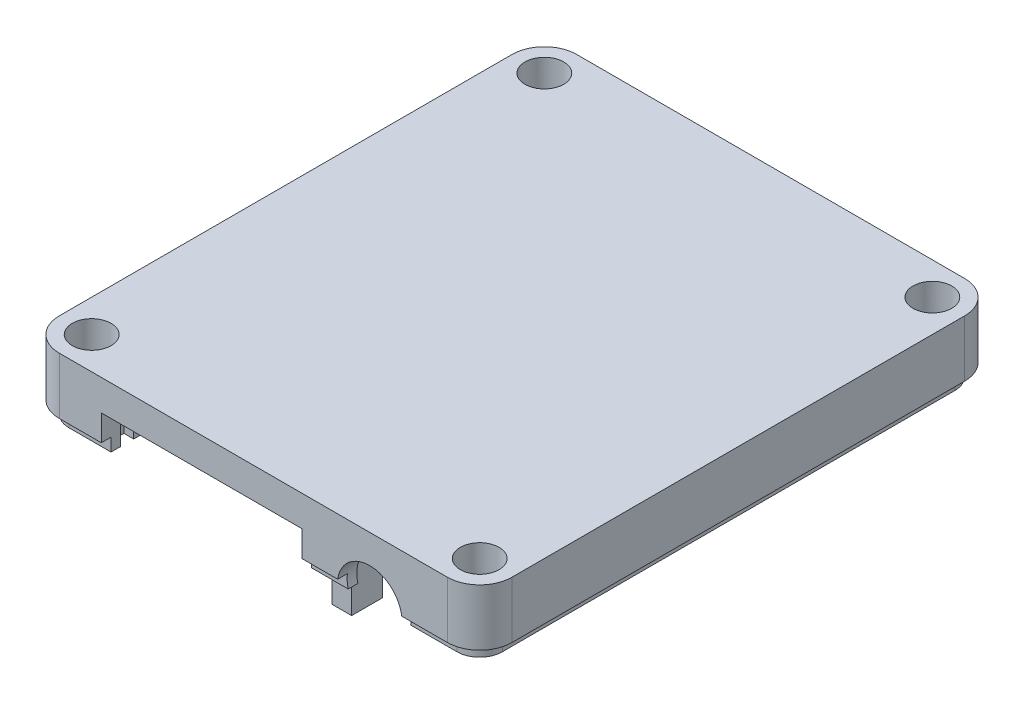
SolidWorks part; units mm, degrees
ref_plane "Front Plane" through (0, 0, 0) normal (0, 0, 1) x (1, 0, 0)
ref_plane "Top Plane" through (0, 0, 0) normal (0, 1, 0) x (1, 0, 0)
ref_plane "Right Plane" through (0, 0, 0) normal (1, 0, 0) x (0, 0, -1)
sketch "Sketch1" plane through (0, 0, 0) normal (0, 1, 0) x (1, 0, 0)
  line L1 (35, -40) -> (-35, -40)
  line L2 (35, -40) -> (35, 40)
  line L3 (35, 40) -> (-35, 40)
  line L4 (-35, -40) -> (-35, 40)
  line L5 (35, -40) -> (-35, 40) construction
  line L6 (35, 40) -> (-35, -40) construction
  point P0 (0, 0)
  dimension "D1" = 70
  dimension "D2" = 80
extrude "Boss-Extrude1" add sketch "Sketch1" along normal blind 21.5
fillet "Fillet1" radius 5 4 edges at (-35, 10.75, -40) (35, 10.75, 40) (-35, 10.75, 40) (35, 10.75, -40)
shell "Shell1" thickness 3
sketch "Sketch3" plane through (0, 21.5, 0) normal (0, 1, 0) x (1, 0, 0)
  circle A0 centre (-30, 35) radius 5
  circle A1 centre (30, 35) radius 5
  circle A2 centre (30, -35) radius 5
  circle A3 centre (-30, -35) radius 5
  arc A4 (-30, 40) -> (-35, 35) centre (-30, 35) ccw construction
  arc A5 (35, 35) -> (30, 40) centre (30, 35) ccw construction
  arc A6 (30, -40) -> (35, -35) centre (30, -35) ccw construction
  arc A7 (-35, -35) -> (-30, -40) centre (-30, -35) ccw construction
extrude "Boss-Extrude2" add sketch "Sketch3" against normal through all
sketch "Sketch2" plane through (0, 0, 0) normal (1, 0, 0) x (0, 0, -1)
  line L0 (-40, 10.75) -> (51.5624, 10.75)
  line L1 (-40, 0) -> (-40, 21.5) construction
split "Split2" trim tools "Sketch2" bodies to split 104 resulting bodies 105 106
sketch "Sketch4" plane through (0, 21.5, 0) normal (0, 1, 0) x (1, 0, 0)
  circle A0 centre (-30, 35) radius 1
  circle A1 centre (30, 35) radius 1
  circle A2 centre (30, -35) radius 1
  circle A3 centre (-30, -35) radius 1
  dimension "D1" = 2
extrude "Cut-Extrude1" cut sketch "Sketch4" against normal through all
sketch "Sketch6" plane through (0, 10.75, 0) normal (0, -1, 0) x (1, 0, 0)
  line L8 (-30, -38.5) -> (30, -38.5)
  line L9 (33.5, -35) -> (33.5, 35)
  line L10 (30, 38.5) -> (-30, 38.5)
  line L11 (-33.5, 35) -> (-33.5, -35)
  line L12 (-30, -38.5) -> (30, -38.5)
  line L13 (33.5, -35) -> (33.5, 35)
  line L14 (30, 38.5) -> (-30, 38.5)
  line L15 (-33.5, 35) -> (-33.5, -35)
  arc A8 (-33.5, -35) -> (-30, -38.5) centre (-30, -35) ccw
  arc A9 (30, -38.5) -> (33.5, -35) centre (30, -35) ccw
  arc A10 (33.5, 35) -> (30, 38.5) centre (30, 35) ccw
  arc A11 (-30, 38.5) -> (-33.5, 35) centre (-30, 35) ccw
  arc A12 (-33.5, -35) -> (-30, -38.5) centre (-30, -35) ccw
  arc A13 (30, -38.5) -> (33.5, -35) centre (30, -35) ccw
  arc A14 (33.5, 35) -> (30, 38.5) centre (30, 35) ccw
  arc A15 (-30, 38.5) -> (-33.5, 35) centre (-30, 35) ccw
  dimension "D1" = 1.5
extrude "Cut-Extrude3" cut sketch "Sketch6" against normal blind 2 flip side to cut
sketch "Sketch7" plane through (0, 10.75, 0) normal (0, 1, 0) x (1, 0, 0)
  line L0 (-30, 40) -> (30, 40) construction
  line L1 (35, 35) -> (35, -35) construction
  line L2 (30, -40) -> (-30, -40) construction
  line L3 (-35, -35) -> (-35, 35) construction
  line L4 (-30, 40) -> (30, 40)
  line L5 (35, 35) -> (35, -35)
  line L6 (30, -40) -> (-30, -40)
  line L7 (-35, -35) -> (-35, 35)
  line L16 (30, 38.7) -> (-30, 38.7)
  line L17 (33.7, -35) -> (33.7, 35)
  line L18 (-30, -38.7) -> (30, -38.7)
  line L19 (-33.7, 35) -> (-33.7, -35)
  line L20 (30, 38.7) -> (-30, 38.7)
  line L21 (33.7, -35) -> (33.7, 35)
  line L22 (-30, -38.7) -> (30, -38.7)
  line L23 (-33.7, 35) -> (-33.7, -35)
  arc A0 (-30, 40) -> (-35, 35) centre (-30, 35) ccw construction
  arc A1 (35, 35) -> (30, 40) centre (30, 35) ccw construction
  arc A2 (30, -40) -> (35, -35) centre (30, -35) ccw construction
  arc A3 (-35, -35) -> (-30, -40) centre (-30, -35) ccw construction
  arc A4 (-30, 40) -> (-35, 35) centre (-30, 35) ccw
  arc A5 (35, 35) -> (30, 40) centre (30, 35) ccw
  arc A6 (30, -40) -> (35, -35) centre (30, -35) ccw
  arc A7 (-35, -35) -> (-30, -40) centre (-30, -35) ccw
  arc A16 (-30, 38.7) -> (-33.7, 35) centre (-30, 35) ccw
  arc A17 (33.7, 35) -> (30, 38.7) centre (30, 35) ccw
  arc A18 (30, -38.7) -> (33.7, -35) centre (30, -35) ccw
  arc A19 (-33.7, -35) -> (-30, -38.7) centre (-30, -35) ccw
  arc A20 (-30, 38.7) -> (-33.7, 35) centre (-30, 35) ccw
  arc A21 (33.7, 35) -> (30, 38.7) centre (30, 35) ccw
  arc A22 (30, -38.7) -> (33.7, -35) centre (30, -35) ccw
  arc A23 (-33.7, -35) -> (-30, -38.7) centre (-30, -35) ccw
  dimension "D1" = 0.2
extrude "Boss-Extrude3" add sketch "Sketch7" along normal offset from surface (1.8 mm away) 0.2 up to face at (0, 12.75, 0)
sketch "Sketch8" plane through (-35, 0, 0) normal (-1, 0, 0) x (0, 0, 1)
  line L1 (35, 12.55) -> (-35, 12.55) construction
  circle A0 centre (-20, 12.05) radius 5.5
  dimension "D1" = 20
  dimension "D2" = 11
  dimension "D3" = 0.5
extrude "Cut-Extrude4" cut sketch "Sketch8" against normal blind 10
sketch "Sketch9" plane through (0, 0, 40) normal (0, 0, 1) x (1, 0, 0)
  line L0 (30, 12.55) -> (-30, 12.55) construction
  line L1 (-20, 16.75) -> (0, 16.75)
  line L2 (-20, 16.75) -> (-20, 4.75)
  line L3 (-20, 4.75) -> (0, 4.75)
  line L4 (0, 16.75) -> (0, 4.75)
  line L5 (-10, 4.75) -> (-10, -9.1876) construction
  line L6 (-30, 21.5) -> (-30, 0) construction
  line L7 (-30, 10.75) -> (0, 10.75) construction
  circle A0 centre (18, 12.05) radius 5
  dimension "D1" = 10
  dimension "D2" = 0.5
  dimension "D3" = 18
  dimension "D4" = 20
  dimension "D5" = 12
  dimension "D6" = 10
extrude "Cut-Extrude5" cut sketch "Sketch9" against normal blind 10
sketch "Sketch11" plane through (0, 18.5, 0) normal (0, -1, 0) x (1, 0, 0)
  line L0 (-20, 38.5) -> (-30, 38.5) construction
  line L1 (-28, 38.5) -> (12, 38.5)
  line L2 (-28, 38.5) -> (-28, 32)
  line L3 (-28, 32) -> (-23.5, 32)
  line L4 (12, 38.5) -> (12, 32)
  line L5 (7.5, 32) -> (12, 32)
  line L6 (-25, 37) -> (9, 37)
  line L7 (-25, 37) -> (-25, 35)
  line L8 (-25, 35) -> (-23.5, 35)
  line L9 (9, 37) -> (9, 35)
  line L11 (-23.5, 35) -> (-23.5, 32)
  line L13 (7.5, 35) -> (7.5, 32)
  line L14 (7.5, 35) -> (9, 35)
  line L15 (-25.4174, 37) -> (25.4174, 37) construction
  arc A1 (-32, 30.4174) -> (-25.4174, 37) centre (-30, 35) ccw construction
  dimension "D1" = 2
  dimension "D2" = 34
  dimension "D3" = 1.5
  dimension "D4" = 1.5
  dimension "D5" = 3
  dimension "D6" = 3
  dimension "D7" = 3
extrude "Boss-Extrude4" add sketch "Sketch11" along normal up to surface (7.75 mm away) up to face at (-28.1123, 10.75, 23.1983)
sketch "Sketch5" plane through (0, 21.5, 0) normal (0, 1, 0) x (1, 0, 0)
  circle A0 centre (-30, 35) radius 3
  circle A1 centre (30, 35) radius 3
  circle A2 centre (30, -35) radius 3
  circle A3 centre (-30, -35) radius 3
  dimension "D1" = 6
extrude "Cut-Extrude2" cut sketch "Sketch5" against normal offset from surface (7.75 mm away) 3 up to face at (6.2221, 10.75, -7.1616)
sketch "Sketch12" plane through (0, 0, 37) normal (0, 0, -1) x (-1, 0, 0)
  line L0 (23.5, 10.75) -> (23.5, 18.5) construction
  line L1 (23.5, 4.75) -> (-7.5, 4.75)
  line L2 (23.5, 4.75) -> (23.5, 16.75)
  line L3 (23.5, 16.75) -> (-7.5, 16.75)
  line L4 (-7.5, 4.75) -> (-7.5, 16.75)
  line L5 (-7.5, 10.75) -> (-7.5, 18.5) construction
  line L6 (0, 16.75) -> (20, 16.75) construction
  line L7 (0, 4.75) -> (20, 4.75) construction
extrude "Cut-Extrude6" cut sketch "Sketch12" against normal blind 10
sketch "Sketch14" plane through (0, 10.75, 0) normal (0, -1, 0) x (1, 0, 0)
  line L2 (13.172, 36.8) -> (7.5, 36.8)
  line L3 (12, 36.8) -> (9, 36.8)
  line L10 (7.5, 38.5) -> (7.5, 37)
  line L11 (7.5, 37) -> (9, 37)
  line L12 (9, 37) -> (9, 35)
  line L13 (9, 35) -> (7.5, 35)
  line L14 (7.5, 35) -> (7.5, 32)
  line L15 (7.5, 32) -> (12, 32)
  line L16 (12, 32) -> (12, 37)
  line L17 (12, 37) -> (13.172, 37)
  line L18 (13.172, 37) -> (13.172, 38.5)
  line L19 (13.172, 38.5) -> (7.5, 38.5)
  line L22 (9, 36.8) -> (9, 35)
  line L23 (9, 35) -> (7.5, 35)
  line L24 (7.5, 35) -> (7.5, 32)
  line L25 (7.5, 32) -> (12, 32)
  line L26 (12, 32) -> (12, 36.8)
  dimension "D2" = 0.2
  dimension "D1" = 0
extrude "Boss-Extrude5" add sketch "Sketch14" along normal blind 5
delete or keep bodies "Body-Delete/Keep 2" type keep bodies bodies 120
